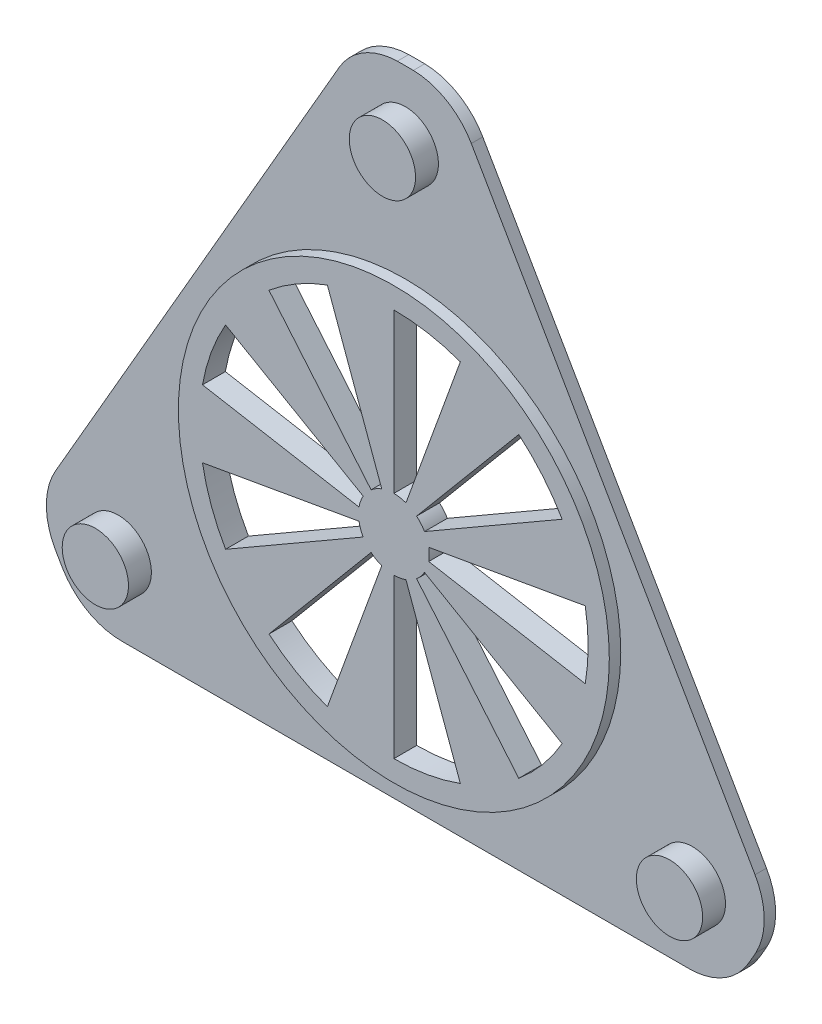
SolidWorks part; units mm, degrees
ref_plane "Спереди" through (0, 0, 0) normal (0, 0, 1) x (1, 0, 0)
ref_plane "Сверху" through (0, 0, 0) normal (0, 1, 0) x (1, 0, 0)
ref_plane "Справа" through (0, 0, 0) normal (1, 0, 0) x (0, 0, -1)
sketch "Sketch1" plane through (0, 0, 0) normal (0, 0, 1) x (1, 0, 0)
  line L0 (3.9, 6.755) -> (7.8, 0) construction
  line L2 (5.85, 10.1325) -> (11.7, 0) construction
  line L4 (7.8, 13.51) -> (15.6, 0) construction
  circle A61 centre (0, 0) radius 20
  circle A131 centre (0, 0) radius 1.25
  circle A484 centre (3.9, 0) radius 1.25
  circle A485 centre (7.8, 0) radius 1.25
  circle A486 centre (11.7, 0) radius 1.25
  circle A487 centre (15.6, 0) radius 1.25
  circle A488 centre (1.95, -3.3775) radius 1.25
  circle A489 centre (3.9, -6.755) radius 1.25
  circle A490 centre (5.85, -10.1325) radius 1.25
  circle A491 centre (7.8, -13.51) radius 1.25
  circle A492 centre (-1.95, -3.3775) radius 1.25
  circle A493 centre (-3.9, -6.755) radius 1.25
  circle A494 centre (-5.85, -10.1325) radius 1.25
  circle A495 centre (-7.8, -13.51) radius 1.25
  circle A496 centre (-3.9, 0) radius 1.25
  circle A497 centre (-7.8, 0) radius 1.25
  circle A498 centre (-11.7, 0) radius 1.25
  circle A499 centre (-15.6, 0) radius 1.25
  circle A500 centre (-1.95, 3.3775) radius 1.25
  circle A501 centre (-3.9, 6.755) radius 1.25
  circle A502 centre (-5.85, 10.1325) radius 1.25
  circle A503 centre (-7.8, 13.51) radius 1.25
  circle A504 centre (1.95, 3.3775) radius 1.25
  circle A505 centre (3.9, 6.755) radius 1.25
  circle A506 centre (5.85, 10.1325) radius 1.25
  circle A507 centre (7.8, 13.51) radius 1.25
  circle A508 centre (5.85, 3.3775) radius 1.25
  circle A509 centre (7.8, 6.755) radius 1.25
  circle A510 centre (9.75, 3.3775) radius 1.25
  circle A511 centre (11.7, 6.755) radius 1.25
  circle A512 centre (9.7491, 10.1341) radius 1.25
  circle A513 centre (13.6509, 3.3759) radius 1.25
  circle A514 centre (5.85, -3.3791) radius 1.25
  circle A515 centre (9.75, -3.3791) radius 1.25
  circle A516 centre (7.8, -6.7566) radius 1.25
  circle A517 centre (11.7, -6.7566) radius 1.25
  circle A518 centre (9.7491, -10.1356) radius 1.25
  circle A519 centre (13.6509, -3.3775) radius 1.25
  circle A520 centre (-0.0013, -6.7573) radius 1.25
  circle A521 centre (1.9487, -10.1348) radius 1.25
  circle A522 centre (-1.9513, -10.1348) radius 1.25
  circle A523 centre (-0.0013, -13.5123) radius 1.25
  circle A524 centre (-3.9032, -13.5123) radius 1.25
  circle A525 centre (3.9005, -13.5123) radius 1.25
  circle A526 centre (-5.8527, -3.3791) radius 1.25
  circle A527 centre (-7.8027, -6.7566) radius 1.25
  circle A528 centre (-9.7527, -3.3791) radius 1.25
  circle A529 centre (-11.7027, -6.7566) radius 1.25
  circle A530 centre (-13.6536, -3.3775) radius 1.25
  circle A531 centre (-9.7518, -10.1356) radius 1.25
  circle A532 centre (-5.8527, 3.3775) radius 1.25
  circle A533 centre (-9.7527, 3.3775) radius 1.25
  circle A534 centre (-7.8027, 6.755) radius 1.25
  circle A535 centre (-11.7027, 6.755) radius 1.25
  circle A536 centre (-9.7518, 10.1341) radius 1.25
  circle A537 centre (-13.6536, 3.3759) radius 1.25
  circle A538 centre (-0.0014, 6.7558) radius 1.25
  circle A539 centre (-1.9514, 10.1333) radius 1.25
  circle A540 centre (1.9486, 10.1333) radius 1.25
  circle A541 centre (-0.0014, 13.5108) radius 1.25
  circle A542 centre (3.9005, 13.5108) radius 1.25
  circle A543 centre (-3.9032, 13.5108) radius 1.25
  circle A544 centre (13.65, -1.1258) radius 2.2517 construction
  circle A545 centre (11.7009, -4.5044) radius 2.2522 construction
  circle A546 centre (9.75, -7.8834) radius 2.2522 construction
  circle A547 centre (7.7987, -11.2591) radius 2.2509 construction
  circle A548 centre (13.65, -1.1258) radius 0.65
  circle A549 centre (11.7009, -4.5044) radius 0.65
  circle A550 centre (9.75, -7.8834) radius 0.65
  circle A551 centre (7.7987, -11.2591) radius 0.65
  circle A552 centre (9.75, -1.1258) radius 0.65
  circle A553 centre (7.8009, -4.5044) radius 0.65
  circle A554 centre (5.85, -7.8834) radius 0.65
  circle A555 centre (3.8987, -11.2591) radius 0.65
  circle A556 centre (5.85, -1.1258) radius 0.65
  circle A557 centre (3.9009, -4.5044) radius 0.65
  circle A558 centre (1.95, -7.8834) radius 0.65
  circle A559 centre (-0.0013, -11.2591) radius 0.65
  circle A560 centre (1.95, -1.1258) radius 0.65
  circle A561 centre (0.0009, -4.5044) radius 0.65
  circle A562 centre (-1.95, -7.8834) radius 0.65
  circle A563 centre (-3.9013, -11.2591) radius 0.65
  circle A564 centre (-1.95, -1.1258) radius 0.65
  circle A565 centre (-3.8991, -4.5044) radius 0.65
  circle A566 centre (-5.85, -7.8834) radius 0.65
  circle A567 centre (-7.8013, -11.2591) radius 0.65
  circle A568 centre (-5.85, -1.1258) radius 0.65
  circle A569 centre (-7.7991, -4.5044) radius 0.65
  circle A570 centre (-9.75, -7.8834) radius 0.65
  circle A572 centre (-9.75, -1.1258) radius 0.65
  circle A573 centre (-11.6991, -4.5044) radius 0.65
  circle A576 centre (-13.65, -1.1258) radius 0.65
  circle A587 centre (0, 2.2517) radius 2.2517 construction
  circle A588 centre (0, 2.2517) radius 0.65
  circle A589 centre (3.9, 2.2517) radius 0.65
  circle A590 centre (7.8, 2.2517) radius 0.65
  circle A591 centre (11.7, 2.2517) radius 0.65
  circle A592 centre (15.6, 2.2517) radius 0.65
  circle A593 centre (1.9491, 5.6297) radius 2.2522 construction
  circle A594 centre (1.9491, 5.6297) radius 0.65
  circle A595 centre (5.8491, 5.6297) radius 0.65
  circle A596 centre (9.7491, 5.6297) radius 0.65
  circle A597 centre (13.6491, 5.6297) radius 0.65
  circle A598 centre (3.8991, 9.0072) radius 2.2522 construction
  circle A599 centre (3.8991, 9.0072) radius 0.65
  circle A600 centre (7.7991, 9.0072) radius 0.65
  circle A601 centre (11.6991, 9.0072) radius 0.65
  circle A602 centre (5.85, 12.3842) radius 2.2517 construction
  circle A603 centre (5.85, 12.3842) radius 0.65
  circle A604 centre (9.75, 12.3842) radius 0.65
  circle A605 centre (5.85, -14.6358) radius 0.65
  circle A606 centre (1.9509, -14.6353) radius 0.65
  circle A607 centre (-1.9491, -14.6353) radius 0.65
  circle A608 centre (-5.85, -14.6358) radius 0.65
  circle A609 centre (-15.6, 2.2517) radius 0.65
  circle A610 centre (-13.65, 5.6281) radius 0.65
  circle A611 centre (-11.7, 9.0056) radius 0.65
  circle A612 centre (-9.75, 12.3842) radius 0.65
  circle A613 centre (-5.85, 12.3842) radius 0.65
  circle A614 centre (-1.95, 12.3842) radius 0.65
  circle A615 centre (1.95, 12.3842) radius 0.65
  circle A616 centre (-7.8, 9.0056) radius 0.65
  circle A617 centre (-9.75, 5.6281) radius 0.65
  circle A618 centre (-11.7, 2.2517) radius 0.65
  circle A619 centre (-3.9, 9.0056) radius 0.65
  circle A620 centre (-5.85, 5.6281) radius 0.65
  circle A621 centre (-7.8, 2.2517) radius 0.65
  circle A622 centre (0, 9.0056) radius 0.65
  circle A623 centre (-1.95, 5.6281) radius 0.65
  circle A624 centre (-3.9, 2.2517) radius 0.65
  circle A625 centre (-15.5991, -4.5044) radius 0.65
  circle A626 centre (-13.65, -7.8834) radius 0.65
  circle A627 centre (-17.55, -7.8834) radius 0.65
  circle A628 centre (-19.5013, -11.2591) radius 0.65
  circle A629 centre (-15.6013, -11.2591) radius 0.65
  circle A630 centre (-11.7013, -11.2591) radius 0.65
  point P51 (0, 0)
  point P125 (-0.0013, -0.0008)
  point P231 (0, 0)
  dimension "D1" = 5
  dimension "D3" = 6
  dimension "D5" = 8
  dimension "D7" = 4
  dimension "D11" = 4
  dimension "D2" = 6
  dimension "D6" = 5
  dimension "D8" = 3
  dimension "D9" = 2
  dimension "D4" = 1.3
  dimension "D10" = 3
ref_plane "Plane1" through (0, 0, 10) normal (0, 0, 1) x (1, 0, 0)
sketch "Sketch2" plane through (0, 0, 10) normal (0, 0, 1) x (1, 0, 0)
  line L0 (0, 3) -> (0, 17)
  line L62 (1.0261, 2.8191) -> (5.8143, 15.9748)
  line L71 (1.9284, 2.2981) -> (10.9274, 13.0228)
  line L92 (2.5981, 1.5) -> (14.7224, 8.5)
  line L101 (2.9544, 0.5209) -> (16.7417, 2.952)
  line L110 (2.9544, -0.5209) -> (16.7417, -2.952)
  line L119 (2.5981, -1.5) -> (14.7224, -8.5)
  line L124 (1.9284, -2.2981) -> (10.9274, -13.0228)
  line L133 (1.0261, -2.8191) -> (5.8143, -15.9748)
  line L142 (0, -3) -> (0, -17)
  line L151 (-1.0261, -2.8191) -> (-5.8143, -15.9748)
  line L160 (-1.9284, -2.2981) -> (-10.9274, -13.0228)
  line L165 (-2.5981, -1.5) -> (-14.7224, -8.5)
  line L168 (-2.9544, -0.5209) -> (-16.7417, -2.952)
  line L171 (-2.9544, 0.5209) -> (-16.7417, 2.952)
  line L174 (-2.5981, 1.5) -> (-14.7224, 8.5)
  line L177 (-1.9284, 2.2981) -> (-10.9274, 13.0228)
  line L180 (-1.0261, 2.8191) -> (-5.8143, 15.9748)
  circle A52 centre (0, 0) radius 17
  circle A53 centre (0, 0) radius 18.85
  circle A199 centre (0, 0) radius 3
  circle A245 centre (0, 0) radius 18.85
  point P39 (0, 0)
  point P108 (0, 0)
  dimension "D1" = 18
extrude "Boss-Extrude1" add sketch "Sketch2" against normal blind 2 contours A53 A52 | A199 L0 A52 L180 | A199 L71 A52 L62 | A199 L101 A52 L92 | A199 L119 A52 L110 | A199 L133 A52 L124 | A199 L151 A52 L142 | A199 L165 A52 L160 | A199 L171 A52 L168 | A199 L177 A52 L174
sketch "Sketch9" plane through (0, 0, 10) normal (0, 0, 1) x (1, 0, 0)
  circle A0 centre (0, 0) radius 3.0981
extrude "Boss-Extrude5" add sketch "Sketch9" against normal up to surface (2 mm away) up to face at (0, 0, 8)
sketch "Sketch3" plane through (0, 0, 8) normal (0, 0, -1) x (-1, 0, 0)
  circle A0 centre (0, 0) radius 17.6
  circle A1 centre (0, 0) radius 35
  circle M33 centre (0, 0) radius 18.85
extrude "Boss-Extrude2" add sketch "Sketch3" against normal blind 1 contours A1 M33
sketch "Sketch4" plane through (0, 0, 8) normal (0, 0, -1) x (-1, 0, 0)
  circle A0 centre (0, 0) radius 29 construction
  circle A1 centre (0, 29) radius 2.9
  circle A2 centre (25.1147, -14.5) radius 2.9
  circle A3 centre (-25.1147, -14.5) radius 2.9
  point P11 (0, 0)
  dimension "D1" = 3
extrude "Boss-Extrude3" add sketch "Sketch4" against normal blind 3
sketch "Sketch6" plane through (0, 0, 9) normal (0, 0, -1) x (-1, 0, 0)
  circle A0 centre (0, 30) radius 5
  circle A2 centre (25.9808, -15) radius 5
  circle A3 centre (-25.9808, -15) radius 5
  point P10 (0, 0)
  dimension "D1" = 3
extrude "Boss-Extrude4" add sketch "Sketch6" along normal blind 1
sketch "Sketch7" plane through (0, 0, 8) normal (0, 0, -1) x (-1, 0, 0)
  line L1 (0, 42) -> (-36.3731, -21)
  line L2 (-36.3731, -21) -> (36.3731, -21)
  line L3 (36.3731, -21) -> (0, 42)
  circle A2 centre (0, 0) radius 21 construction
  circle A3 centre (0, 0) radius 59.1314
extrude "Cut-Extrude1" cut sketch "Sketch7" against normal blind 10
fillet "Fillet1" radius 6 6 edges at (-32.1865, -13.7487, 8.5) (-4.1865, 34.7487, 8.5) (28, -21, 8.5) (-28, -21, 8.5) (4.1865, 34.7487, 8.5) (32.1865, -13.7487, 8.5)
